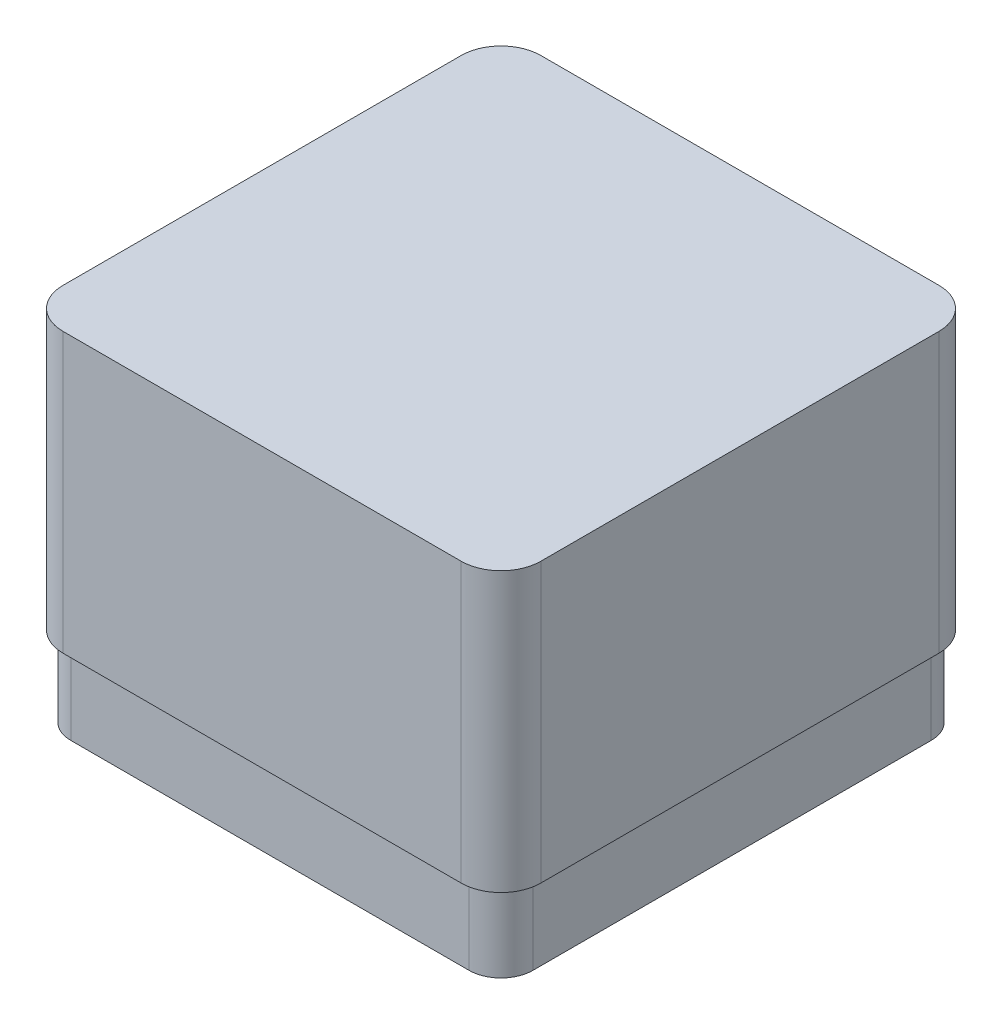
SolidWorks part; units mm, degrees
ref_plane "前视基准面" through (0, 0, 0) normal (0, 0, 1) x (1, 0, 0)
ref_plane "上视基准面" through (0, 0, 0) normal (0, 1, 0) x (1, 0, 0)
ref_plane "右视基准面" through (0, 0, 0) normal (1, 0, 0) x (0, 0, -1)
other "Configuration Table"
sketch "草图1" plane through (0, 0, 0) normal (0, 1, 0) x (1, 0, 0)
  line L1 (0, 0) -> (120, 0)
  line L2 (0, 0) -> (0, 120)
  line L3 (0, 120) -> (120, 120)
  line L4 (120, 0) -> (120, 120)
  dimension "D1" = 120
  dimension "D2" = 120
extrude "凸台-拉伸1" add sketch "草图1" along normal blind 90
fillet "圆角1" radius 10 4 edges at (120, 45, 0) (0, 45, 0) (0, 45, -120) (120, 45, -120)
shell "抽壳1" thickness 4
sketch "草图13" plane through (0, 0, 0) normal (0, -1, 0) x (1, 0, 0)
  line L0 (118, -110) -> (118, -10)
  line L1 (110, -2) -> (10, -2)
  line L2 (2, -10) -> (2, -110)
  line L3 (10, -118) -> (110, -118)
  line L4 (120, -110) -> (120, -10)
  line L5 (110, 0) -> (10, 0)
  line L6 (0, -10) -> (0, -110)
  line L7 (10, -120) -> (110, -120)
  line L8 (120, -110) -> (120, -10)
  line L9 (110, 0) -> (10, 0)
  line L10 (0, -10) -> (0, -110)
  line L11 (10, -120) -> (110, -120)
  arc A0 (118, -10) -> (110, -2) centre (110, -10) ccw
  arc A1 (10, -2) -> (2, -10) centre (10, -10) ccw
  arc A2 (2, -110) -> (10, -118) centre (10, -110) ccw
  arc A3 (110, -118) -> (118, -110) centre (110, -110) ccw
  arc A4 (120, -10) -> (110, 0) centre (110, -10) ccw
  arc A5 (10, 0) -> (0, -10) centre (10, -10) ccw
  arc A6 (0, -110) -> (10, -120) centre (10, -110) ccw
  arc A7 (110, -120) -> (120, -110) centre (110, -110) ccw
  arc A8 (120, -10) -> (110, 0) centre (110, -10) ccw
  arc A9 (10, 0) -> (0, -10) centre (10, -10) ccw
  arc A10 (0, -110) -> (10, -120) centre (10, -110) ccw
  arc A11 (110, -120) -> (120, -110) centre (110, -110) ccw
  dimension "D1" = 0
extrude "切除-拉伸1" cut sketch "草图13" against normal blind 20
